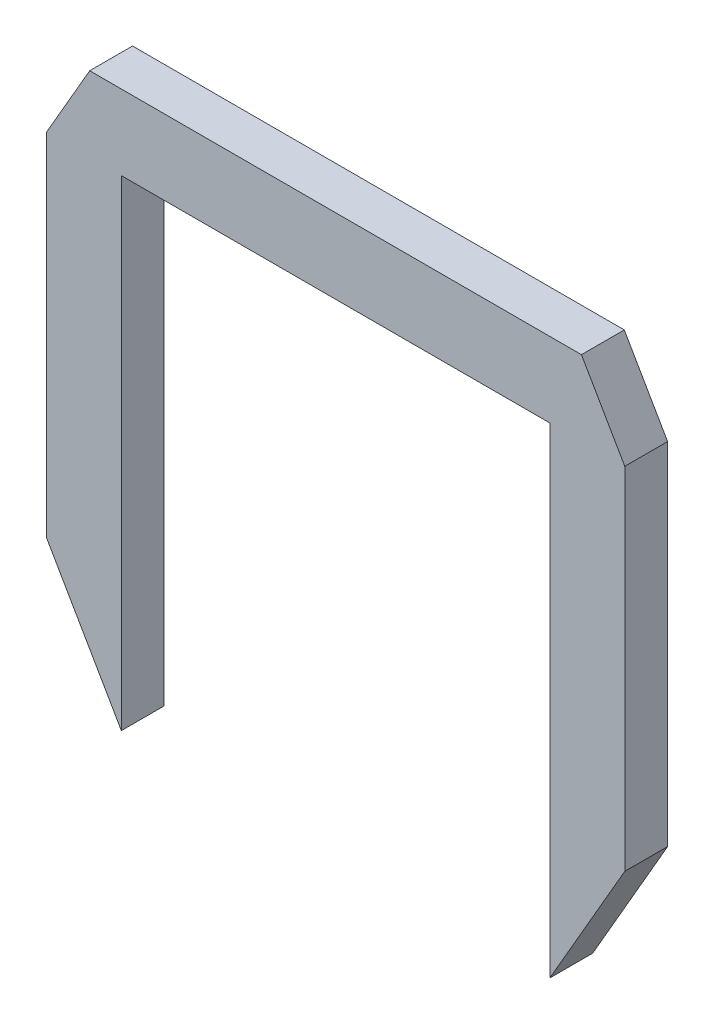
SolidWorks part; units mm, degrees
ref_plane "Front Plane" through (0, 0, 0) normal (0, 0, 1) x (1, 0, 0)
ref_plane "Top Plane" through (0, 0, 0) normal (0, 1, 0) x (1, 0, 0)
ref_plane "Right Plane" through (0, 0, 0) normal (1, 0, 0) x (0, 0, -1)
sketch "Sketch1" plane through (0, 0, 0) normal (0, 0, 1) x (1, 0, 0)
  line L0 (-20, -21.7654) -> (-27, -9.641)
  line L1 (-20, 23.1129) -> (20, 23.1129)
  line L2 (-20, 23.1129) -> (-20, -16.8871)
  line L4 (20, 23.1129) -> (20, -16.8871)
  line L5 (27, 23.107) -> (22.9552, 30.1129)
  line L6 (22.9552, 30.1129) -> (-22.9585, 30.1129)
  line L7 (-27, -9.641) -> (-27, 23.1129)
  line L11 (27, 23.107) -> (27, -9.641)
  line L12 (20, -16.8871) -> (20, -21.7654)
  line L13 (20, -21.7654) -> (27, -9.641)
  line L14 (-20, -16.8871) -> (-20, -21.7654)
  line L15 (-22.9585, 30.1129) -> (-27, 23.1129)
  point P0 (0, 0)
  dimension "D1" = 40
  dimension "D2" = 30
  dimension "D3" = 30
  dimension "D4" = 0
  dimension "D5" = 30
  dimension "D6" = 30
  dimension "D7" = 40
  dimension "D8" = 7
  dimension "D9" = 4.8782
  dimension "D10" = 40
extrude "Boss-Extrude1" add sketch "Sketch1" along normal blind 4
